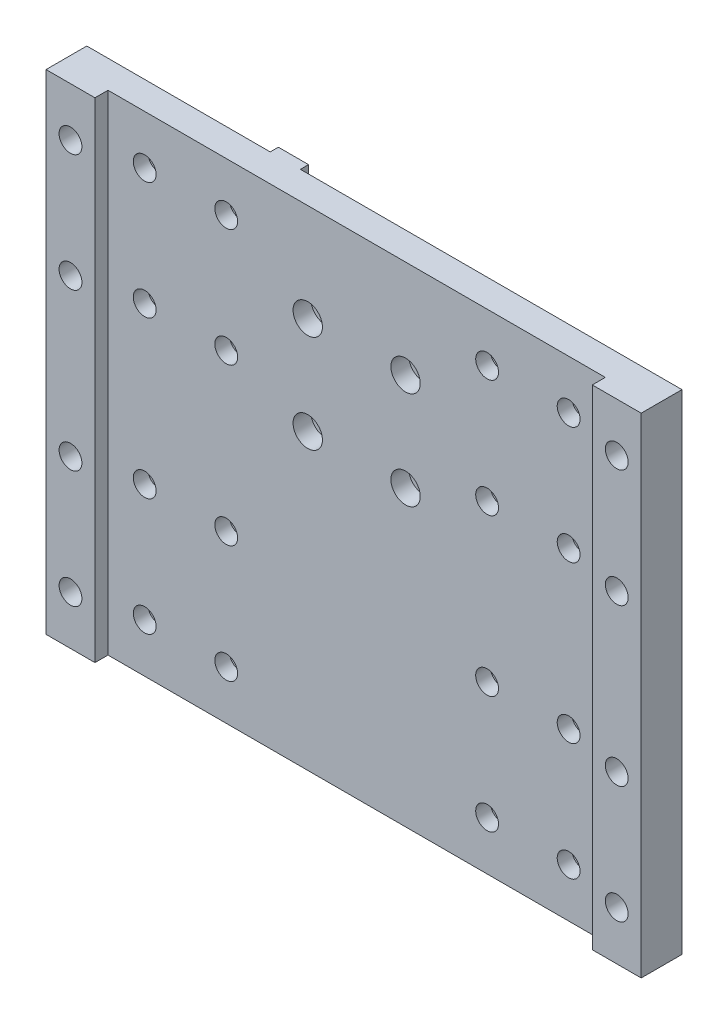
SolidWorks part; units mm, degrees
ref_plane "Front" through (0, 0, 0) normal (0, 0, 1) x (1, 0, 0)
ref_plane "Top" through (0, 0, 0) normal (0, 1, 0) x (1, 0, 0)
ref_plane "Right" through (0, 0, 0) normal (1, 0, 0) x (0, 0, -1)
sketch "Sketch1" plane through (0, 0, 0) normal (0, 0, 1) x (1, 0, 0)
  line L1 (-365, 0) -> (0, 0)
  line L2 (-365, 0) -> (-365, 300)
  line L3 (-365, 300) -> (0, 300)
  line L4 (0, 0) -> (0, 300)
  dimension "D1" = 365
  dimension "D2" = 300
extrude "Boss-Extrude1" add sketch "Sketch1" against normal blind 30
sketch "Sketch2" plane through (0, 0, -30) normal (0, 0, -1) x (-1, 0, 0)
  line L0 (365, 0) -> (0, 0) construction
  line L1 (0, 300) -> (234, 300)
  line L2 (0, 300) -> (0, 0)
  line L3 (0, 0) -> (234, 0)
  line L4 (234, 300) -> (234, 0)
  line L5 (0, 300) -> (365, 300) construction
  line L6 (252.5, 300) -> (365, 300)
  line L7 (252.5, 300) -> (252.5, 0)
  line L8 (252.5, 0) -> (365, 0)
  line L9 (365, 300) -> (365, 0)
  dimension "D1" = 112.5
  dimension "D2" = 18.5
extrude "Cut-Extrude1" cut sketch "Sketch2" against normal blind 5
sketch "Sketch3" plane through (0, 0, 0) normal (0, 0, 1) x (1, 0, 0)
  line L0 (0, 300) -> (-365, 300) construction
  line L1 (-335, 300) -> (-30, 300)
  line L2 (-335, 300) -> (-335, 0)
  line L3 (-335, 0) -> (-30, 0)
  line L4 (-30, 300) -> (-30, 0)
  line L5 (-365, 0) -> (0, 0) construction
  line L6 (0, 0) -> (0, 300) construction
  dimension "D1" = 305
  dimension "D2" = 30
extrude "Cut-Extrude2" cut sketch "Sketch3" against normal blind 8
hole_wizard "CBORE for M12 Socket Head Cap Screw1" positions "Sketch5" profile "Sketch4" counterbore size "M12" standard "JIS" end condition through all
sketch "Sketch5" plane through (-5.9334, 68.0214, -25) normal (0, 0, 1) x (1, 0, 0)
  line L0 (-24.0666, -68.0214) -> (5.9334, -68.0214) construction
  line L1 (5.9334, -68.0214) -> (5.9334, 231.9786) construction
  point P0 (-9.0666, 201.9786)
  point P1 (-9.0666, 129.9786)
  point P3 (-9.0666, 33.9786)
  point P5 (-9.0666, -38.0214)
  dimension "D1" = 30
  dimension "D2" = 72
  dimension "D3" = 96
  dimension "D4" = 72
  dimension "D5" = 15
sketch "Sketch4" plane through (-15, 270, -25) normal (1, 0, 0) x (0, 1, 0)
  line L0 (0, 0) -> (0, 25)
  line L1 (0, 25) -> (7, 25)
  line L3 (7, 25) -> (7, 14)
  line L4 (7, 14) -> (10, 14)
  line L5 (10, 14) -> (10, 0)
  line L7 (10, 0) -> (0, 0)
  line L11 (0, -6.35) -> (0, 107.95) construction
  dimension "Thru Hole Dia." = 14
  dimension "Thru Hole Depth" = 25
  dimension "C'Bore Dia." = 20
  dimension "C'Bore Depth" = 14
pattern_linear "LPattern1" count 2 spacing 335 along (-1, 0, 0) of "CBORE for M12 Socket Head Cap Screw1"
hole_wizard "CBORE for M8 Socket Head Cap Screw1" positions "Sketch7" profile "Sketch6" counterbore size "M8" standard "JIS" end condition through all
sketch "Sketch7" plane through (0, 0, -8) normal (0, 0, 1) x (1, 0, 0)
  line L0 (0, 0) -> (0, 300) construction
  line L1 (-335, 0) -> (-30, 0) construction
  point P0 (-52.5, 30)
  point P1 (-52.5, 102)
  point P3 (-102.5, 102)
  point P5 (-102.5, 30)
  dimension "D1" = 52.5
  dimension "D2" = 30
  dimension "D3" = 50
  dimension "D4" = 72
sketch "Sketch6" plane through (-52.5, 30, -8) normal (1, 0, 0) x (0, -1, 0)
  line L0 (0, 0) -> (0, 22)
  line L1 (0, 22) -> (4.5, 22)
  line L3 (4.5, 22) -> (4.5, 9)
  line L4 (4.5, 9) -> (7, 9)
  line L5 (7, 9) -> (7, 0)
  line L7 (7, 0) -> (0, 0)
  line L11 (0, -6.35) -> (0, 107.95) construction
  dimension "Thru Hole Dia." = 9
  dimension "Thru Hole Depth" = 22
  dimension "C'Bore Dia." = 14
  dimension "C'Bore Depth" = 9
pattern_linear "LPattern2" count 2 spacing 210 along (-1, 0, 0) count 2 spacing 168 along (0, 1, 0) of "CBORE for M8 Socket Head Cap Screw1"
hole_wizard "CBORE for M10 Socket Head Cap Screw1" positions "Sketch9" profile "Sketch8" counterbore size "M10" standard "JIS" end condition through all
sketch "Sketch9" plane through (0, 0, -8) normal (0, 0, 1) x (1, 0, 0)
  line L0 (-335, 0) -> (-30, 0) construction
  line L1 (0, 0) -> (0, 300) construction
  point P0 (-152.5, 240)
  point P1 (-152.5, 180)
  point P3 (-212.5, 180)
  point P5 (-212.5, 240)
  dimension "D1" = 180
  dimension "D2" = 152.5
  dimension "D3" = 60
  dimension "D4" = 60
sketch "Sketch8" plane through (-152.5, 240, -8) normal (1, 0, 0) x (0, -1, 0)
  line L0 (0, 0) -> (0, 22)
  line L1 (0, 22) -> (6, 22)
  line L3 (6, 22) -> (6, 11)
  line L4 (6, 11) -> (9, 11)
  line L5 (9, 11) -> (9, 0)
  line L7 (9, 0) -> (0, 0)
  line L11 (0, -6.35) -> (0, 107.95) construction
  dimension "Thru Hole Dia." = 12
  dimension "Thru Hole Depth" = 22
  dimension "C'Bore Dia." = 18
  dimension "C'Bore Depth" = 11
